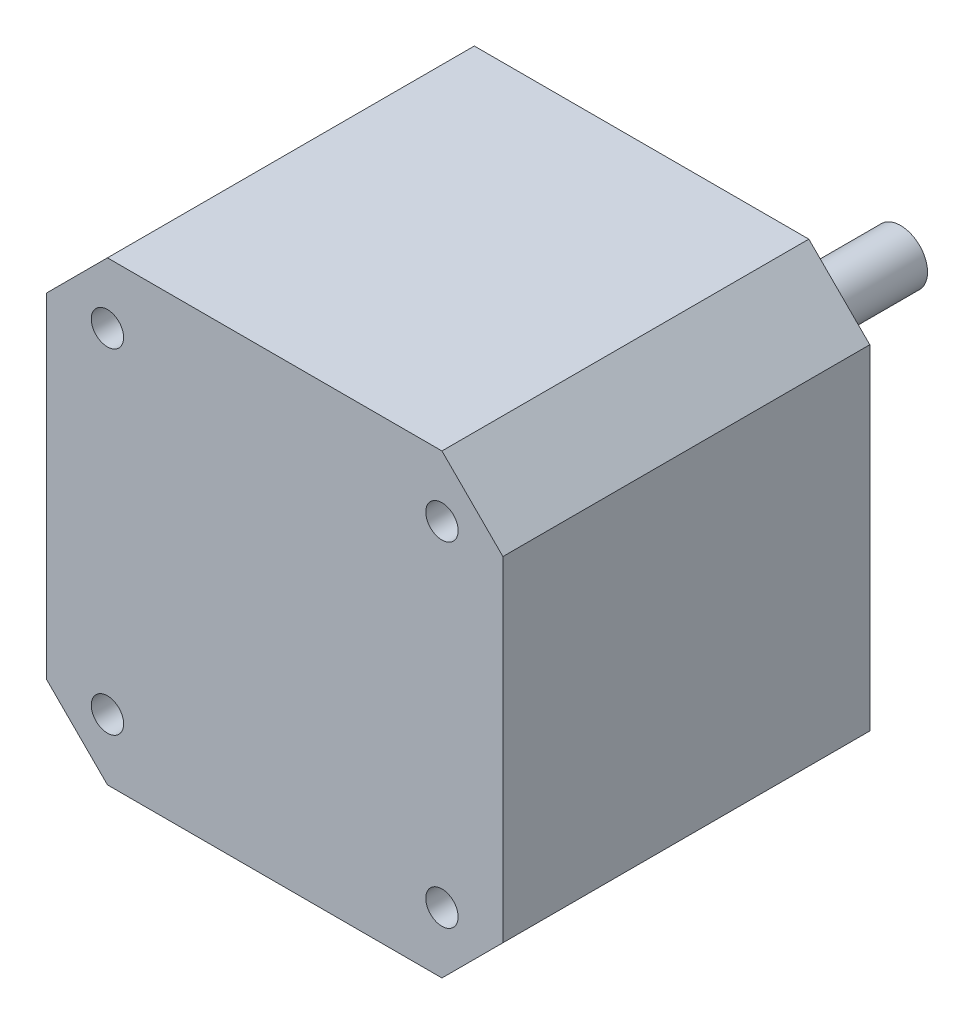
SolidWorks part; units mm, degrees
ref_plane "Front Plane" through (0, 0, 0) normal (0, 0, 1) x (1, 0, 0)
ref_plane "Top Plane" through (0, 0, 0) normal (0, 1, 0) x (1, 0, 0)
ref_plane "Right Plane" through (0, 0, 0) normal (1, 0, 0) x (0, 0, -1)
sketch "Sketch1" plane through (0, 0, 0) normal (0, 0, 1) x (1, 0, 0)
  line L0 (-15.5, 21.15) -> (-21.15, 15.5)
  line L1 (-15.5, -21.15) -> (15.5, -21.15)
  line L2 (-21.15, -15.5) -> (-21.15, 15.5)
  line L3 (-15.5, 21.15) -> (15.5, 21.15)
  line L4 (21.15, -15.5) -> (21.15, 15.5)
  line L13 (21.15, 15.5) -> (15.5, 21.15)
  line L14 (15.5, -21.15) -> (21.15, -15.5)
  line L15 (-21.15, -15.5) -> (-15.5, -21.15)
  circle A0 centre (15.5, 15.5) radius 1.5
  circle A1 centre (15.5, -15.5) radius 1.5
  circle A2 centre (-15.5, -15.5) radius 1.5
  circle A3 centre (-15.5, 15.5) radius 1.5
  point P0 (0, 0)
  point P6 (0, 0)
  point P21 (0, 0)
  point P30 (0, 0)
  dimension "D1" = 4
  dimension "D2" = 4
extrude "Boss-Extrude1" add sketch "Sketch1" along normal blind 34
sketch "Sketch3" plane through (0, 0, 0) normal (1, 0, 0) x (0, 0, -1)
  line L0 (0, 0) -> (24, 0)
  line L1 (24, 0) -> (24, 2.5)
  line L2 (24, 2.5) -> (2, 2.5)
  line L3 (2, 2.5) -> (2, 11)
  line L4 (2, 11) -> (0, 11)
  line L5 (0, 15.5) -> (0, -15.5) construction
  line L6 (0, 11) -> (0, 0)
revolve "Revolve1" add sketch "Sketch3" angle 360 about L0
